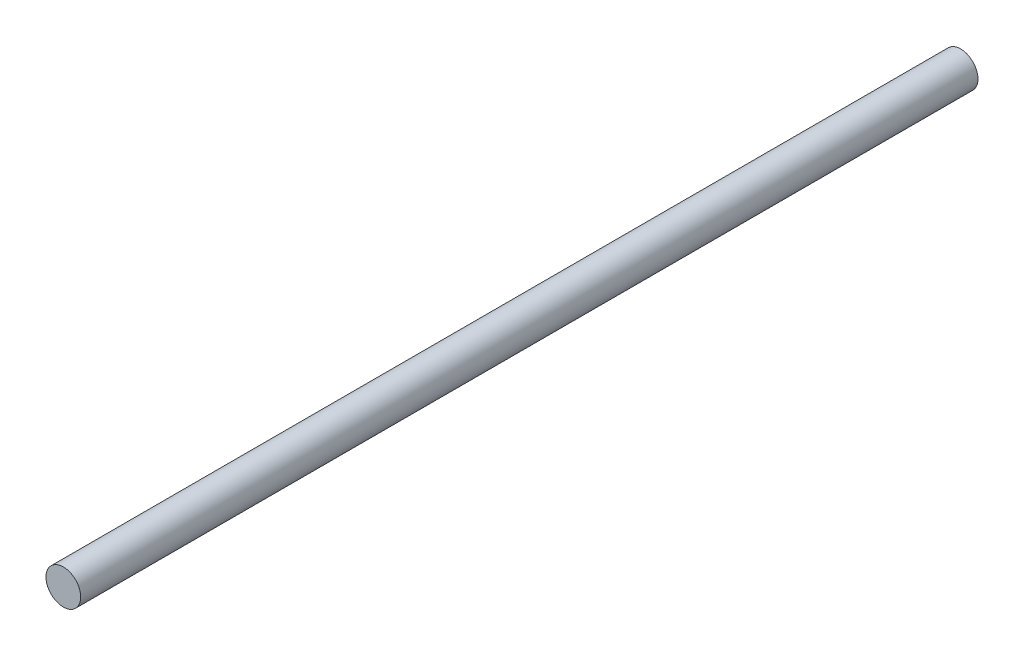
SolidWorks part; units mm, degrees
ref_plane "Front Plane" through (0, 0, 0) normal (0, 0, 1) x (1, 0, 0)
ref_plane "Top Plane" through (0, 0, 0) normal (0, 1, 0) x (1, 0, 0)
ref_plane "Right Plane" through (0, 0, 0) normal (1, 0, 0) x (0, 0, -1)
sketch "Sketch1" plane through (0, 0, 0) normal (0, 0, 1) x (1, 0, 0)
  circle A0 centre (0, 0) radius 6
extrude "Boss-Extrude1" add sketch "Sketch1" along normal blind 310
